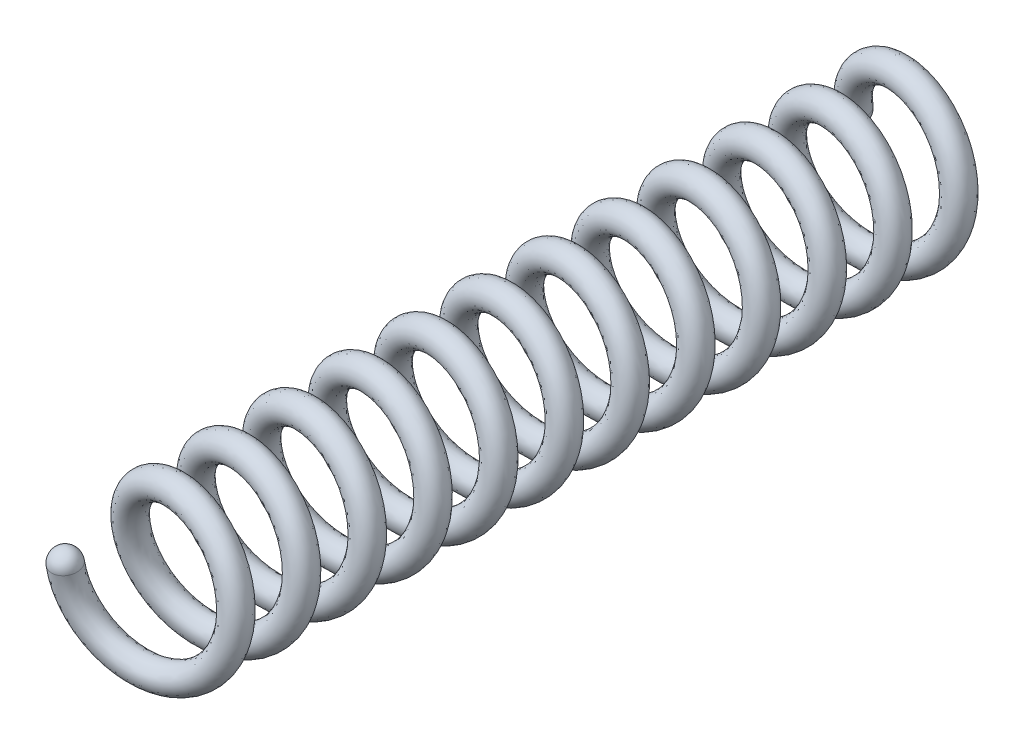
SolidWorks part; units mm, degrees
material "AISI 1020"
ref_plane "Front Plane" through (0, 0, 0) normal (0, 0, 1) x (1, 0, 0)
ref_plane "Top Plane" through (0, 0, 0) normal (0, 1, 0) x (1, 0, 0)
ref_plane "Right Plane" through (0, 0, 0) normal (1, 0, 0) x (0, 0, -1)
sketch "Sketch3" plane through (0, 0, 0) normal (0, 0, 1) x (1, 0, 0)
  circle A0 centre (0, 0) radius 25
curve "Helix/Spiral4" pitch 24 height 288 turns 12
sweep "Sweep1" add path "Helix/Spiral4" circular profile diameter 10 parameters "D3"=10
sketch3d "3DSketch2" plane through (0, 0, 0) normal (0, 0, 1) x (1, 0, 0)
sketch "Sketch45" plane through (0, 0, 0) normal (0, 0.9885, 0.151) x (1, 0, 0)
  line L0 (-21.8915, -3.9163) -> (-28.1085, 3.9163)
  arc A0 (-21.8915, -3.9163) -> (-28.1085, 3.9163) centre (-25, 0) ccw
  circle A1 centre (-25, 0) radius 5 construction
revolve "Revolve4" add sketch "Sketch45" angle 180 about L0
sketch3d "3DSketch3" plane through (0, 0, 0) normal (0, 0, 1) x (1, 0, 0)
sketch "Sketch47" plane through (0, 42.9994, 6.5698) normal (0, -0.9885, -0.151) x (-1, 0, 0)
  line L0 (29.9966, -284.5114) -> (20.0034, -284.8809)
  circle A0 centre (25, -284.6961) radius 5 construction
  arc A1 (29.9966, -284.5114) -> (20.0034, -284.8809) centre (25, -284.6961) cw
revolve "Revolve5" add sketch "Sketch47" angle 180 about L0
